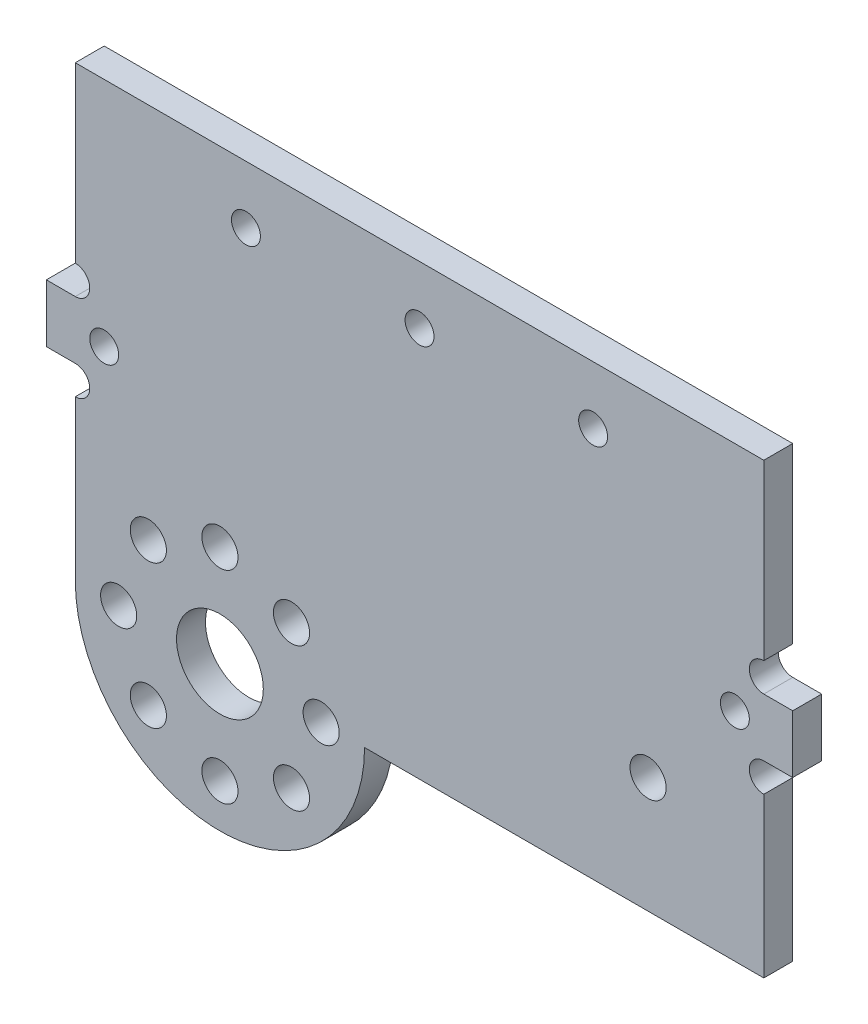
SolidWorks part; units mm, degrees
material "自訂玻璃纖維"
ref_plane "前基準面" through (0, 0, 0) normal (0, 0, 1) x (1, 0, 0)
ref_plane "上基準面" through (0, 0, 0) normal (0, 1, 0) x (1, 0, 0)
ref_plane "右基準面" through (0, 0, 0) normal (1, 0, 0) x (0, 0, -1)
sketch "草圖1" plane through (0, 0, 0) normal (0, 0, 1) x (1, 0, 0)
  line L0 (-7.5875, -13.118) -> (18.0581, -13.118)
  line L1 (-28.5419, 9.882) -> (-28.5419, 10.882)
  line L2 (-28.5419, 9.882) -> (-28.5419, 5.882)
  line L3 (-8.5419, -13.118) -> (-7.5875, -13.118)
  line L4 (19.0581, 9.882) -> (19.0581, 5.882)
  line L5 (19.0581, 10.882) -> (19.0581, 9.882)
  line L6 (-28.5419, 10.882) -> (-28.5419, 16.882)
  line L7 (-27.5419, 17.882) -> (18.0581, 17.882)
  line L8 (19.0581, 16.882) -> (19.0581, 10.882)
  line L9 (18.0581, -13.118) -> (19.0581, -13.118)
  line L10 (19.0581, -13.118) -> (19.0581, -12.118)
  line L11 (-27.5419, 17.882) -> (-28.5419, 17.882)
  line L12 (-28.5419, 17.882) -> (-28.5419, 16.882)
  line L13 (18.0581, 17.882) -> (19.0581, 17.882)
  line L14 (19.0581, 17.882) -> (19.0581, 16.882)
  line L15 (-28.5419, -2.118) -> (-28.5419, -13.118)
  line L16 (-28.5419, 3.882) -> (-30.5419, 3.882)
  line L17 (19.0581, -2.118) -> (19.0581, -12.118)
  line L18 (-28.5419, -0.118) -> (-30.5419, -0.118)
  line L19 (-30.5419, 3.882) -> (-30.5419, -0.118)
  line L20 (21.0581, 3.882) -> (21.0581, -0.118)
  line L21 (19.0581, -0.118) -> (21.0581, -0.118)
  line L22 (19.0581, 3.882) -> (21.0581, 3.882)
  circle A0 centre (-18.5419, -13.118) radius 3
  circle A1 centre (-18.5419, -6.118) radius 1.25
  circle A2 centre (-13.5922, -8.1682) radius 1.25
  circle A3 centre (-11.5419, -13.118) radius 1.25
  circle A4 centre (-13.5922, -18.0677) radius 1.25
  circle A5 centre (-18.5419, -20.118) radius 1.25
  circle A6 centre (-23.4917, -18.0677) radius 1.25
  circle A7 centre (-25.5419, -13.118) radius 1.25
  circle A8 centre (-23.4917, -8.1682) radius 1.25
  arc A9 (-28.5419, -13.118) -> (-8.5419, -13.118) centre (-18.5419, -13.118) ccw
  arc A10 (-28.5419, 3.882) -> (-28.5419, 5.882) centre (-28.5419, 4.882) ccw
  arc A11 (-28.5419, -0.118) -> (-28.5419, -2.118) centre (-28.5419, -1.118) cw
  arc A12 (19.0581, -0.118) -> (19.0581, -2.118) centre (19.0581, -1.118) ccw
  arc A13 (19.0581, 3.882) -> (19.0581, 5.882) centre (19.0581, 4.882) cw
  circle A14 centre (-26.5419, 1.882) radius 1
  circle A15 centre (17.0581, 1.882) radius 1
  circle A16 centre (-4.7419, 13.882) radius 1
  circle A17 centre (11.0581, -5.118) radius 1.25
  circle A18 centre (-16.7419, 13.882) radius 1
  circle A19 centre (7.2581, 13.882) radius 1
  point P24 (-18.5419, -13.118)
  point P31 (19.0581, 10.882)
  point P34 (-28.5419, 10.882)
  point P37 (-28.5419, 11.882)
  point P48 (-28.5419, 17.882)
  dimension "D3" = 6
  dimension "D4" = 2.5
  dimension "D5" = 7
  dimension "D6" = 8
  dimension "D8" = 4
  dimension "D7" = 2
  dimension "D10" = 2
  dimension "D11" = 24
  dimension "D12" = 12
  dimension "D13" = 4
  dimension "D14" = 2
  dimension "D15" = 2
  dimension "D16" = 4
  dimension "D17" = 2.5
  dimension "D18" = 8
  dimension "D19" = 8
  dimension "D21" = 4
  dimension "D1" = 47.6
  dimension "D2" = 24
  dimension "D9" = 2
  dimension "D20" = 7
extrude "填料-伸長2" add sketch "草圖1" along normal blind 2
